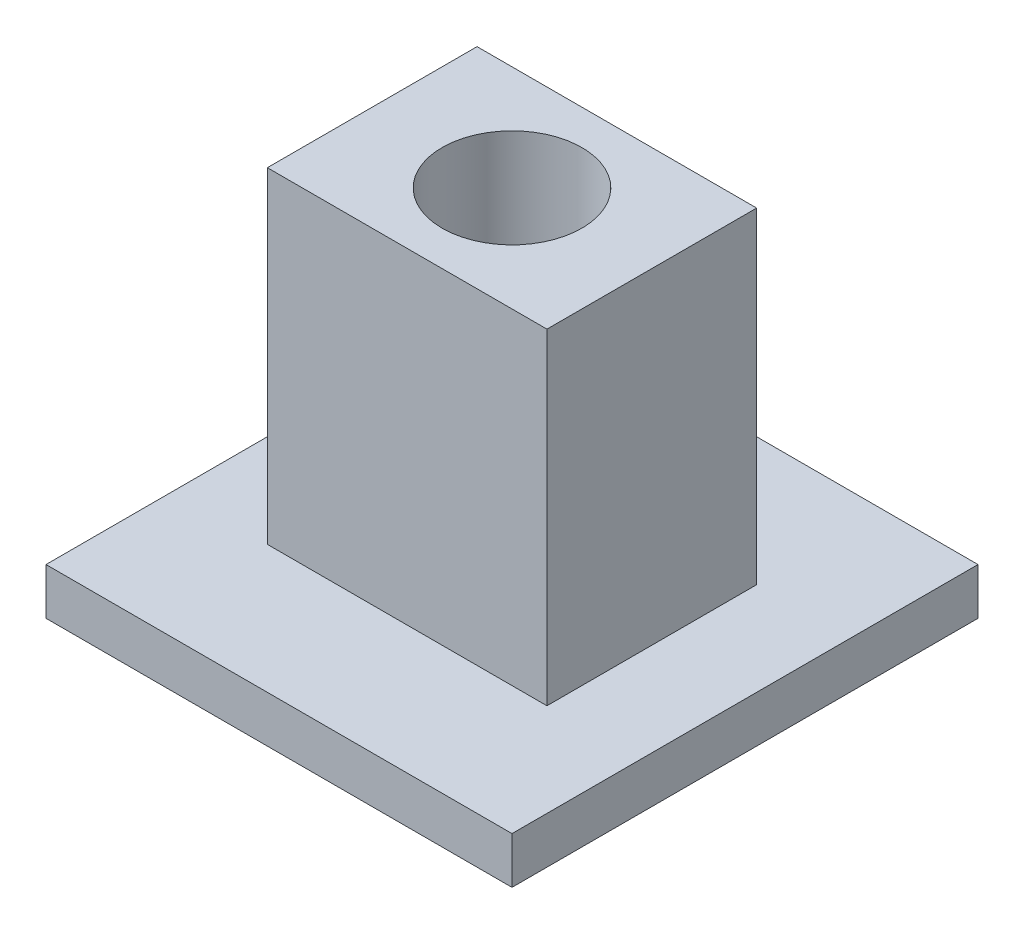
SolidWorks part; units mm, degrees
ref_plane "前视基准面" through (0, 0, 0) normal (0, 0, 1) x (1, 0, 0)
ref_plane "上视基准面" through (0, 0, 0) normal (0, 1, 0) x (1, 0, 0)
ref_plane "右视基准面" through (0, 0, 0) normal (1, 0, 0) x (0, 0, -1)
sketch "草图1" plane through (0, 0, 0) normal (0, 1, 0) x (1, 0, 0)
  line L1 (-10, -10) -> (10, -10)
  line L2 (-10, -10) -> (-10, 10)
  line L3 (-10, 10) -> (10, 10)
  line L4 (10, -10) -> (10, 10)
  line L5 (-10, -10) -> (10, 10) construction
  line L6 (-10, 10) -> (10, -10) construction
  point P0 (0, 0)
  dimension "D1" = 20
  dimension "D2" = 20
extrude "凸台-拉伸1" add sketch "草图1" along normal blind 2
sketch "草图2" plane through (0, 2, 0) normal (0, 1, 0) x (1, 0, 0)
  line L1 (-6, -4.5) -> (6, -4.5)
  line L2 (-6, -4.5) -> (-6, 4.5)
  line L3 (-6, 4.5) -> (6, 4.5)
  line L4 (6, -4.5) -> (6, 4.5)
  line L5 (-6, -4.5) -> (6, 4.5) construction
  line L6 (-6, 4.5) -> (6, -4.5) construction
  circle A0 centre (0, 0) radius 3
  point P0 (0, 0)
  dimension "D3" = 6
  dimension "D1" = 9
  dimension "D2" = 12
extrude "凸台-拉伸2" add sketch "草图2" along normal blind 14
